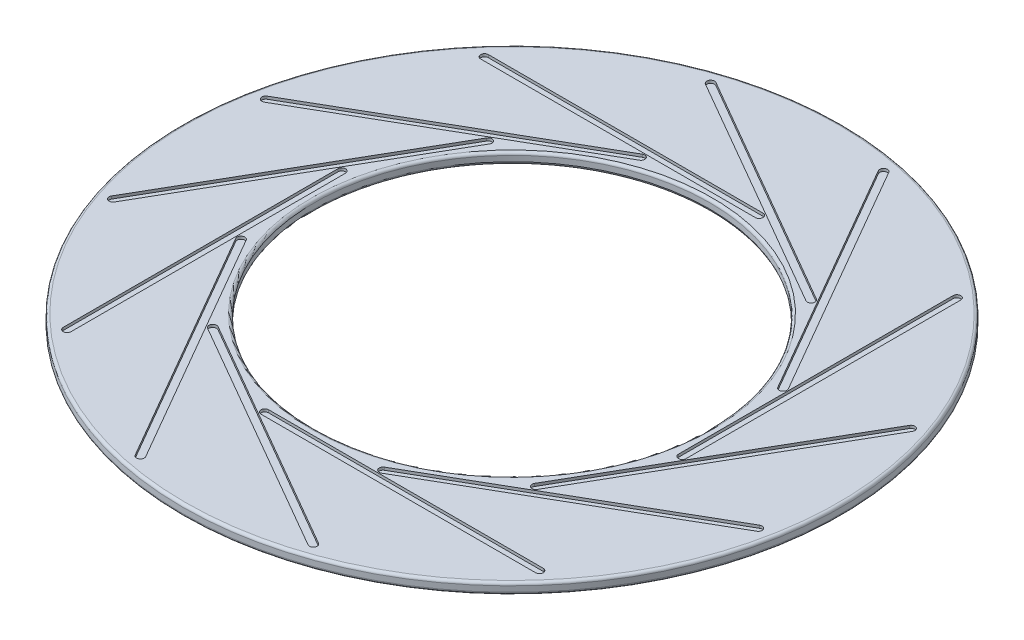
SolidWorks part; units mm, degrees
ref_plane "Front Plane" through (0, 0, 0) normal (0, 0, 1) x (1, 0, 0)
ref_plane "Top Plane" through (0, 0, 0) normal (0, 1, 0) x (1, 0, 0)
ref_plane "Right Plane" through (0, 0, 0) normal (1, 0, 0) x (0, 0, -1)
sketch "Sketch2" plane through (0, 0, 0) normal (0, 1, 0) x (1, 0, 0)
  circle A0 centre (0, 0) radius 36
  circle A1 centre (0, 0) radius 60
  dimension "D1" = 72
  dimension "D2" = 120
extrude "ring extrusion" add sketch "Sketch2" along normal blind 2
sketch "Sketch5" plane through (0, 2, 0) normal (0, 1, 0) x (1, 0, 0)
  line L0 (0, 60) -> (0, 0) construction
  line L1 (-43, 38) -> (7, 38) construction
  line L2 (-43, 38.7) -> (7, 38.7)
  line L3 (-43, 37.3) -> (7, 37.3)
  circle A0 centre (0, 0) radius 38 construction
  arc A1 (-43, 38.7) -> (-43, 37.3) centre (-43, 38) ccw
  arc A2 (7, 37.3) -> (7, 38.7) centre (7, 38) ccw
  circle A3 centre (0, 0) radius 60 construction
  point P6 (-18, 38)
  dimension "D1" = 76
  dimension "D2" = 0.7
  dimension "D3" = 50
  dimension "D4" = 7
extrude "grooves" cut sketch "Sketch5" against normal blind 0.5
pattern_circular "CirPattern2" count 12 over 360 about axis through (0, 0, 0) along (0, 1, 0) of "grooves"
fillet "Fillet3" radius 0.5 4 edges at (0, 2, 60) (0, 0, 60) (0, 2, 36) (0, 0, 36)
equation "\"D1@CirPattern2\"=\"grooves@Shutter Assembly.Assembly\""
